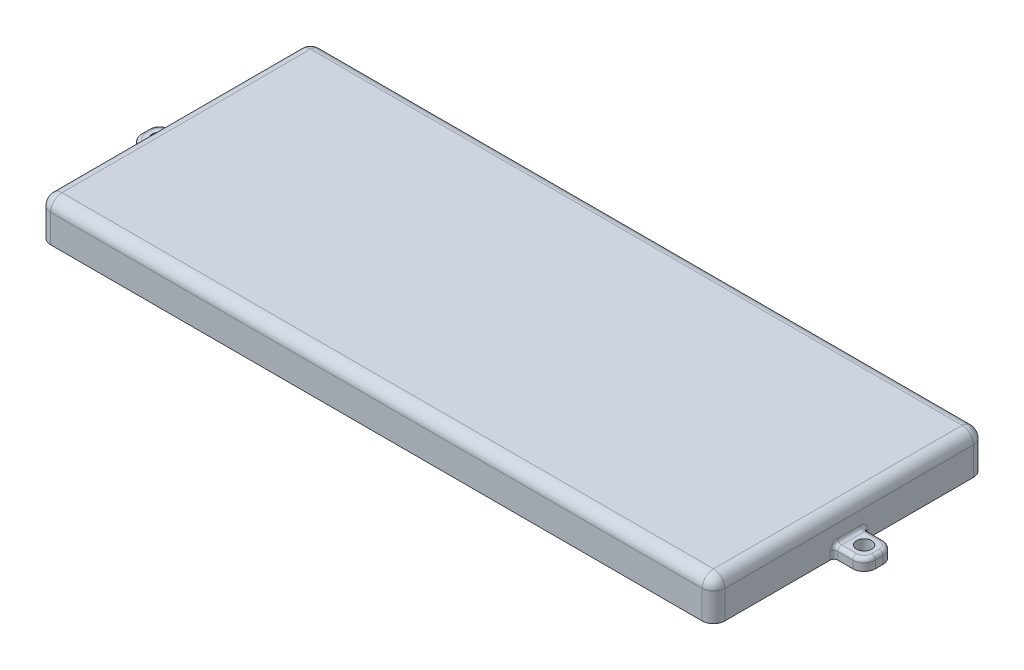
SolidWorks part; units mm, degrees
ref_plane "Front Plane" through (0, 0, 0) normal (0, 0, 1) x (1, 0, 0)
ref_plane "Top Plane" through (0, 0, 0) normal (0, 1, 0) x (1, 0, 0)
ref_plane "Right Plane" through (0, 0, 0) normal (1, 0, 0) x (0, 0, -1)
sketch "Sketch1" plane through (0, 0, 0) normal (0, 1, 0) x (1, 0, 0)
  line L1 (-89.5, 36) -> (89.5, 36)
  line L2 (-89.5, 36) -> (-89.5, -36)
  line L3 (-89.5, -36) -> (89.5, -36)
  line L4 (89.5, 36) -> (89.5, -36)
  line L5 (0, -36) -> (0, 36) construction
  line L6 (-89.5, 0) -> (89.5, 0) construction
  point P0 (0, 0)
  dimension "D1" = 72
  dimension "D2" = 179
extrude "Boss-Extrude1" add sketch "Sketch1" along normal blind 10.5
shell "Shell1" thickness 3
sketch "Sketch2" plane through (-89.5, 0, 0) normal (-1, 0, 0) x (0, 0, 1)
  line L0 (-36, 0) -> (36, 0) construction
  line L1 (-4, 0) -> (4, 0)
  line L2 (-4, 0) -> (-4, 3)
  line L3 (-4, 3) -> (4, 3)
  line L4 (4, 0) -> (4, 3)
  line L5 (-36, 10.5) -> (-36, 0) construction
  dimension "D1" = 8
  dimension "D2" = 3
  dimension "D3" = 32
extrude "Boss-Extrude2" add sketch "Sketch2" along normal blind 8
sketch "Sketch3" plane through (89.5, 0, 0) normal (1, 0, 0) x (0, 0, -1)
  line L0 (-36, 0) -> (36, 0) construction
  line L1 (-4, 0) -> (4, 0)
  line L2 (-4, 0) -> (-4, 3)
  line L3 (-4, 3) -> (4, 3)
  line L4 (4, 0) -> (4, 3)
  line L5 (-36, 10.5) -> (-36, 0) construction
  dimension "D1" = 8
  dimension "D2" = 3
  dimension "D3" = 32
extrude "Boss-Extrude3" add sketch "Sketch3" along normal blind 8
sketch "Sketch4" plane through (0, 3, 0) normal (0, 1, 0) x (1, 0, 0)
  line L0 (-97.5, 4) -> (-89.5, -4) construction
  line L1 (-97.5, -4) -> (-89.5, 4) construction
  circle A0 centre (-93.5, 0) radius 2
  dimension "D1" = 4
extrude "Cut-Extrude1" cut sketch "Sketch4" against normal blind 8
sketch "Sketch5" plane through (0, 3, 0) normal (0, 1, 0) x (1, 0, 0)
  line L0 (89.5, 4) -> (97.5, -4) construction
  line L1 (89.5, -4) -> (97.5, 4) construction
  circle A0 centre (93.5, 0) radius 2
  dimension "D1" = 4
extrude "Cut-Extrude2" cut sketch "Sketch5" against normal blind 8
fillet "Fillet1" radius 3 16 edges at (-86.5, 3.75, -33) (-86.5, 3.75, 33) (86.5, 3.75, -33) (86.5, 3.75, 33) (97.5, 1.5, 4) (97.5, 1.5, -4) (89.5, 5.25, -36) (89.5, 5.25, 36) (-89.5, 5.25, -36) (-89.5, 5.25, 36) (-97.5, 1.5, -4) (-97.5, 1.5, 4) (0, 10.5, 36) (-89.5, 10.5, 0) (0, 10.5, -36) (89.5, 10.5, 0)
fillet "Fillet2" radius 1 16 edges at (-89.5, 1.5, -4) (-89.5, 3, 0) (-89.5, 1.5, 4) (89.5, 1.5, 4) (89.5, 1.5, -4) (89.5, 3, 0) (92, 3, 4) (92, 3, -4) (96.6213, 3, -3.1213) (97.5, 3, 0) (-92, 3, 4) (-96.6213, 3, 3.1213) (-92, 3, -4) (-96.6213, 3, -3.1213) (96.6213, 3, 3.1213) (-97.5, 3, 0)
